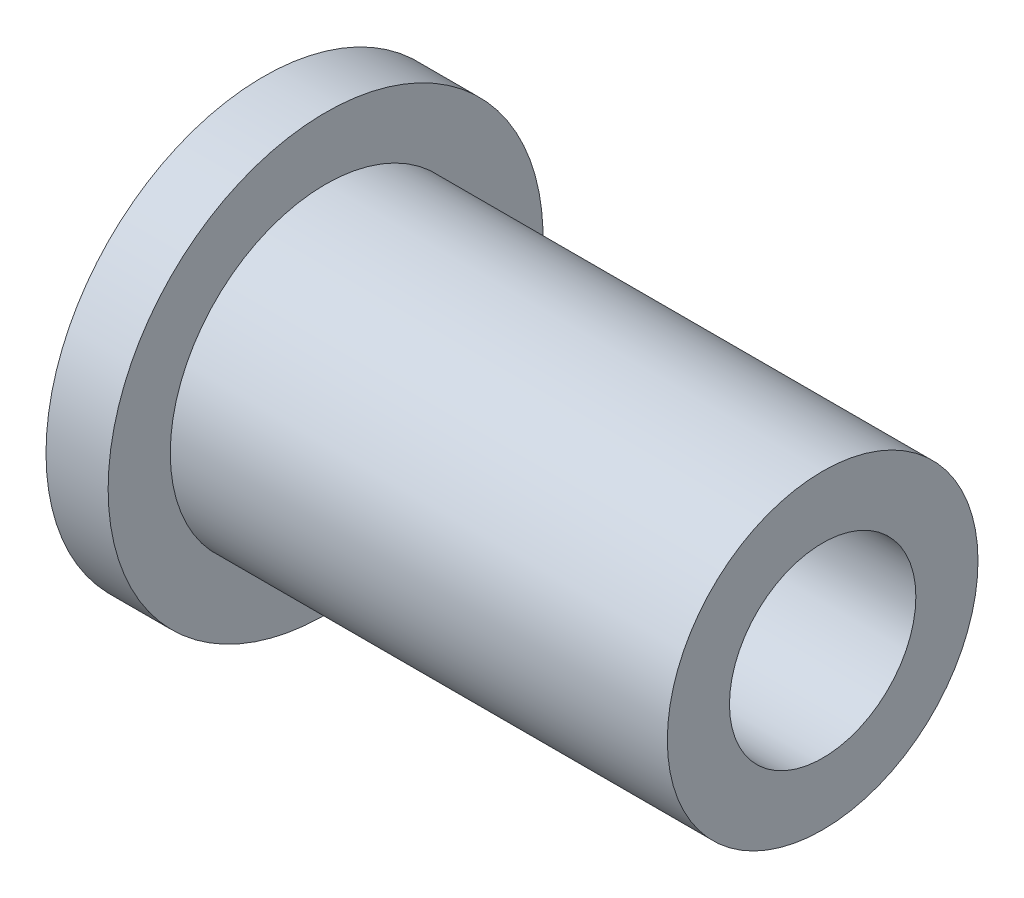
SolidWorks part; units mm, degrees
ref_plane "Front Plane" through (0, 0, 0) normal (0, 0, 1) x (1, 0, 0)
ref_plane "Top Plane" through (0, 0, 0) normal (0, 1, 0) x (1, 0, 0)
ref_plane "Right Plane" through (0, 0, 0) normal (1, 0, 0) x (0, 0, -1)
sketch "Sketch2" plane through (0, 0, 0) normal (1, 0, 0) x (0, 0, -1)
  circle A0 centre (0, 0) radius 2.3812
  circle A1 centre (0, 0) radius 3.9688
  dimension "D1" = 4.7625
  dimension "D2" = 7.9375
extrude "Boss-Extrude1" add sketch "Sketch2" along normal blind 12.7
sketch "Sketch3" plane through (0, 0, 0) normal (-1, 0, 0) x (0, 0, 1)
  circle A0 centre (0, 0) radius 2.3812
  circle A1 centre (0, 0) radius 5.5562
  dimension "D1" = 4.7625
  dimension "D2" = 11.1125
extrude "Boss-Extrude2" add sketch "Sketch3" along normal blind 1.5875
